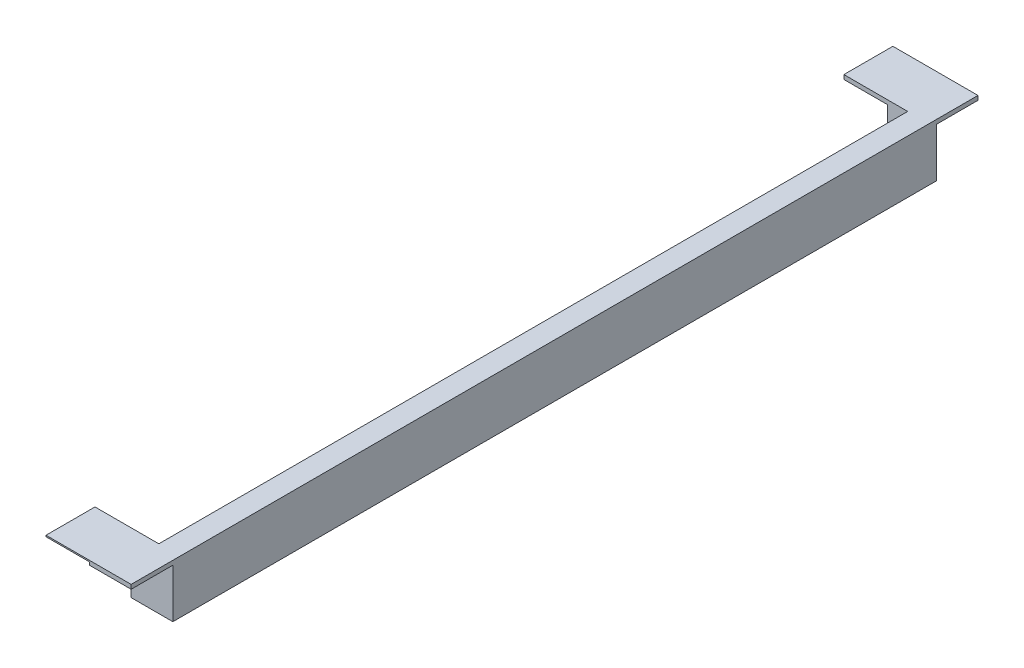
SolidWorks part; units mm, degrees
ref_plane "前视基准面" through (0, 0, 0) normal (0, 0, 1) x (1, 0, 0)
ref_plane "上视基准面" through (0, 0, 0) normal (0, 1, 0) x (1, 0, 0)
ref_plane "右视基准面" through (0, 0, 0) normal (1, 0, 0) x (0, 0, -1)
sketch "草图2" plane through (0, 0, 0) normal (0, 1, 0) x (1, 0, 0)
  line L1 (-14.4929, 79.7445) -> (83.5071, 79.7445)
  line L2 (-14.4929, 79.7445) -> (-14.4929, -18.2555)
  line L3 (-14.4929, -18.2555) -> (83.5071, -18.2555)
  line L4 (83.5071, 79.7445) -> (83.5071, -18.2555)
extrude "凸台-拉伸1" add sketch "草图2" along normal blind 10
sketch "草图3" plane through (0, 0, 18.2555) normal (0, 0, 1) x (1, 0, 0)
  line L1 (-14.4929, 10) -> (83.5071, 10)
  line L2 (-14.4929, 10) -> (-14.4929, -115)
  line L3 (-14.4929, -115) -> (83.5071, -115)
  line L4 (83.5071, 10) -> (83.5071, -115)
extrude "凸台-拉伸2" add sketch "草图3" along normal blind 10
sketch "草图4" plane through (0, 0, 28.2555) normal (0, 0, 1) x (1, 0, 0)
  line L0 (-14.4929, 10) -> (-14.4929, -115) construction
  line L1 (83.5071, -115) -> (-14.4929, -115)
  line L2 (83.5071, -115) -> (83.5071, -52.5)
  line L3 (83.5071, -52.5) -> (-14.4929, -52.5)
  line L4 (-14.4929, -115) -> (-14.4929, -52.5)
extrude "凸台-拉伸3" add sketch "草图4" along normal blind 886.75
mirror "镜向4" about plane through (0, 0, 915.0055) normal (0, 0, 1) of bodies 108
sketch "草图5" plane through (0, 0, 28.2555) normal (0, 0, 1) x (1, 0, 0)
  line L1 (-14.4929, 10) -> (83.5071, 10)
  line L2 (-14.4929, 10) -> (-14.4929, -52.5)
  line L3 (-14.4929, -52.5) -> (83.5071, -52.5)
  line L4 (83.5071, 10) -> (83.5071, -52.5)
extrude "凸台-拉伸4" add sketch "草图5" along normal blind 7.1
sketch "草图6" plane through (0, 0, 1801.7555) normal (0, 0, -1) x (-1, 0, 0)
  line L1 (-83.5071, 10) -> (14.4929, 10)
  line L2 (-83.5071, 10) -> (-83.5071, -52.5)
  line L3 (-83.5071, -52.5) -> (14.4929, -52.5)
  line L4 (14.4929, 10) -> (14.4929, -52.5)
extrude "凸台-拉伸5" add sketch "草图6" along normal blind 7.1
sketch "草图9" plane through (-14.4929, 0, 0) normal (-1, 0, 0) x (0, 0, 1)
  line L0 (35.3555, 10) -> (35.3555, -52.5) construction
  line L1 (-79.7445, 10) -> (35.3555, 10)
  line L2 (-79.7445, 10) -> (-79.7445, 0)
  line L3 (-79.7445, 0) -> (35.3555, 0)
  line L4 (35.3555, 10) -> (35.3555, 0)
  line L10 (1909.7555, 10) -> (1909.7555, 0) construction
  line L11 (1794.6555, 10) -> (1909.7555, 10)
  line L12 (1794.6555, 10) -> (1794.6555, 6.8)
  line L13 (1794.6555, 6.8) -> (1909.7555, 6.8)
  line L14 (1909.7555, 10) -> (1909.7555, 6.8)
extrude "凸台-拉伸6" add sketch "草图9" along normal blind 102
sketch "草图11" plane through (0, -52.5, 0) normal (0, 1, 0) x (1, 0, 0)
  line L0 (83.5071, -1794.6555) -> (-14.4929, -1794.6555) construction
  line L1 (83.5071, -35.3555) -> (33.5071, -35.3555)
  line L2 (83.5071, -35.3555) -> (83.5071, -1794.6555)
  line L3 (83.5071, -1794.6555) -> (33.5071, -1794.6555)
  line L4 (33.5071, -35.3555) -> (33.5071, -1794.6555)
extrude "凸台-拉伸7" add sketch "草图11" along normal up to surface (62.5 mm away) up to face at (-16.4929, 10, -22.1945)
